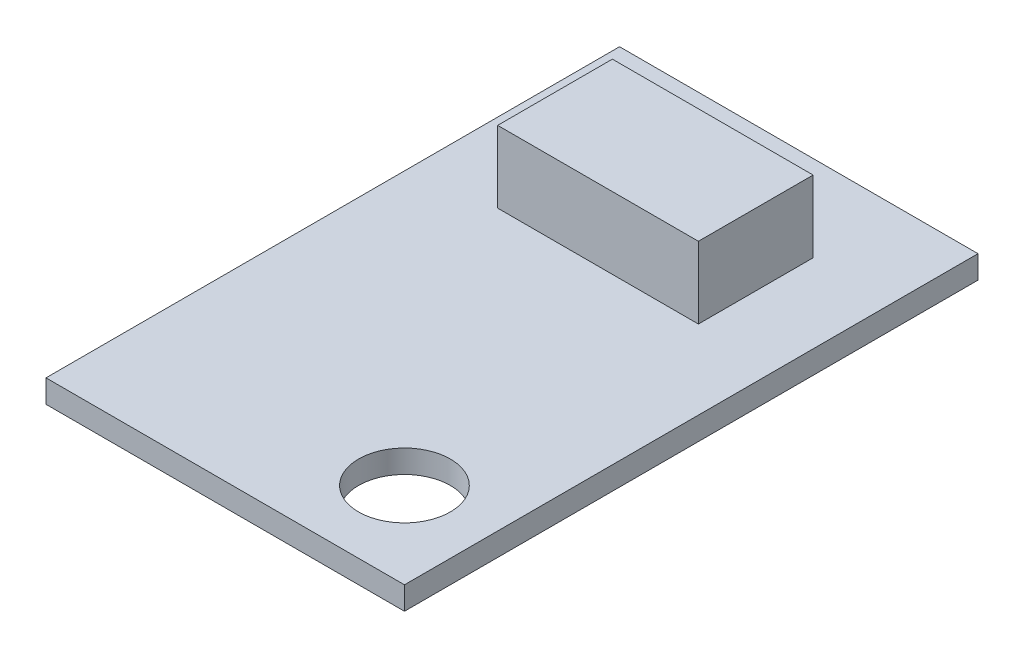
SolidWorks part; units mm, degrees
ref_plane "Front Plane" through (0, 0, 0) normal (0, 0, 1) x (1, 0, 0)
ref_plane "Top Plane" through (0, 0, 0) normal (0, 1, 0) x (1, 0, 0)
ref_plane "Right Plane" through (0, 0, 0) normal (1, 0, 0) x (0, 0, -1)
sketch "Sketch1" plane through (0, 0, 0) normal (0, 1, 0) x (1, 0, 0)
  line L1 (-6.25, 0) -> (6.25, 0)
  line L2 (-6.25, 0) -> (-6.25, 20)
  line L3 (-6.25, 20) -> (6.25, 20)
  line L4 (6.25, 0) -> (6.25, 20)
  circle A0 centre (3.25, 3) radius 1.6
  dimension "D3" = 3.2
  dimension "D1" = 12.5
  dimension "D2" = 20
  dimension "D4" = 3
  dimension "D5" = 3
extrude "Boss-Extrude1" add sketch "Sketch1" along normal blind 0.8
sketch "Sketch2" plane through (0, 0.8, 0) normal (0, 1, 0) x (1, 0, 0)
  line L0 (0, 0) -> (0, 50000) construction
  line L1 (-3.5, 17) -> (3.5, 17)
  line L2 (-3.5, 17) -> (-3.5, 13)
  line L3 (-3.5, 13) -> (3.5, 13)
  line L4 (3.5, 17) -> (3.5, 13)
  line L5 (-6.25, 0) -> (6.25, 0) construction
  line L6 (6.25, 20) -> (-6.25, 20) construction
  point P8 (0, 0)
  dimension "D1" = 7
  dimension "D2" = 4
  dimension "D3" = 3
extrude "Boss-Extrude2" add sketch "Sketch2" along normal blind 2.5
